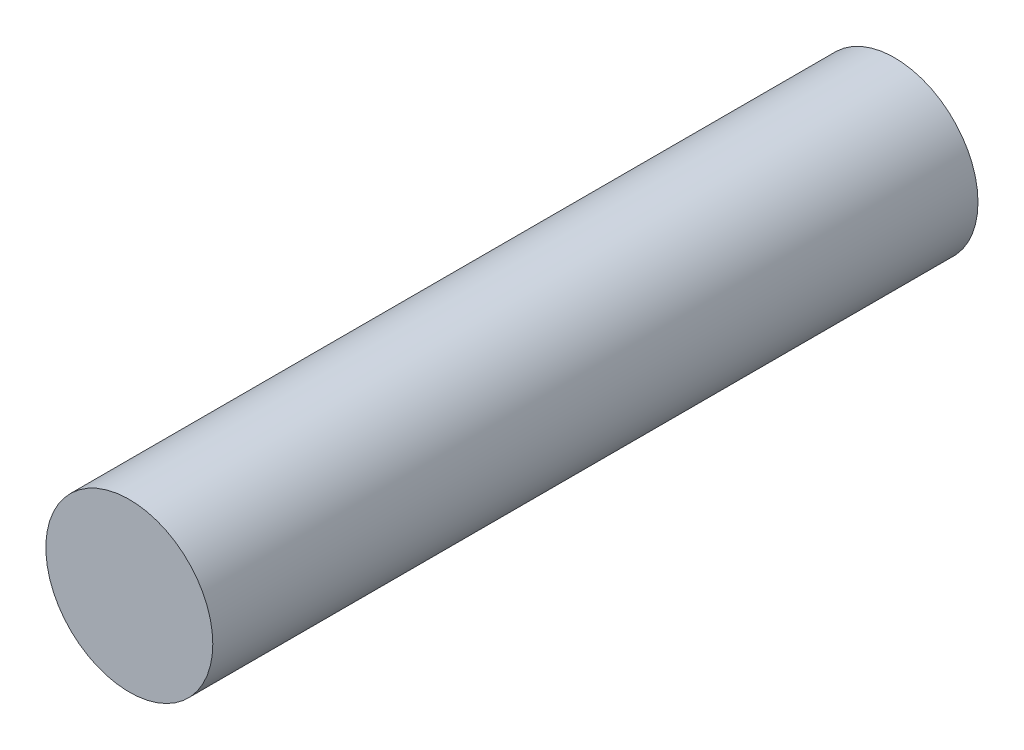
SolidWorks part; units mm, degrees
ref_plane "Alzado" through (0, 0, 0) normal (0, 0, 1) x (1, 0, 0)
ref_plane "Planta" through (0, 0, 0) normal (0, 1, 0) x (1, 0, 0)
ref_plane "Vista lateral" through (0, 0, 0) normal (1, 0, 0) x (0, 0, -1)
sketch "Croquis1" plane through (0, 0, 0) normal (0, 0, 1) x (1, 0, 0)
  circle A0 centre (0, 0) radius 6
  dimension "D1" = 12
extrude "Saliente-Extruir1" add sketch "Croquis1" along normal blind 55
